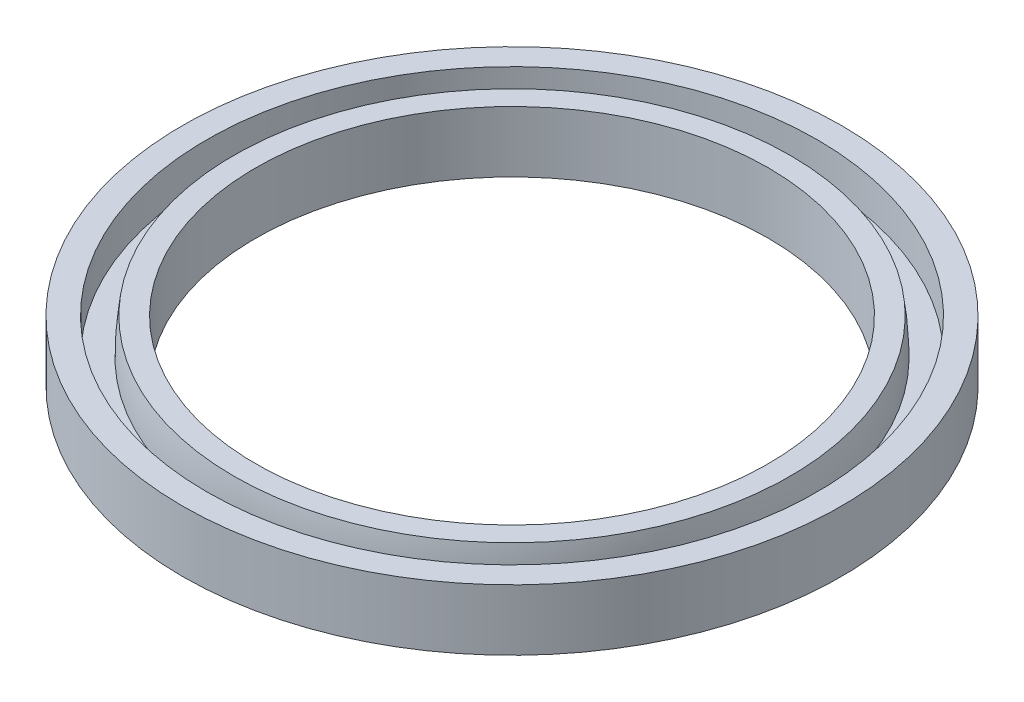
SolidWorks part; units mm, degrees
ref_plane "Front Plane" through (0, 0, 0) normal (0, 0, 1) x (1, 0, 0)
ref_plane "Top Plane" through (0, 0, 0) normal (0, 1, 0) x (1, 0, 0)
ref_plane "Right Plane" through (0, 0, 0) normal (1, 0, 0) x (0, 0, -1)
sketch "Sketch1" plane through (0, 0, 0) normal (1, 0, 0) x (0, 0, -1)
  line L0 (0, -564.5896) -> (0, 27664.8881) construction
  line L1 (-564.5896, 0) -> (27664.8881, 0) construction
  line L2 (25, 3) -> (27, 3)
  line L3 (21, 3) -> (22.7785, 3)
  line L4 (21, 3) -> (21, -2)
  line L5 (21, -2) -> (27, -2)
  line L6 (27, 3) -> (27, -2)
  line L9 (23, 0) -> (25, 0)
  line L10 (25, 3) -> (25, 0)
  line L11 (22.7785, 3) -> (22.8206, 3) construction
  arc A2 (25, 0) -> (0, 25) centre (0, 0) ccw construction
  arc A3 (23, 0) -> (0, 23) centre (0, 0) ccw construction
  arc A5 (22.7785, 3) -> (23, 0) centre (2.5724, 0) cw
  point P14 (22.8035, 3)
  point P16 (0, 0)
  point P20 (0, 0)
  dimension "D1" = 6
  dimension "D6" = 0.025
  dimension "D4" = 2
  dimension "D2" = 5
  dimension "D3" = 2
  dimension "D5" = 2
revolve "Revolve1" add sketch "Sketch1" angle 360 about L0
